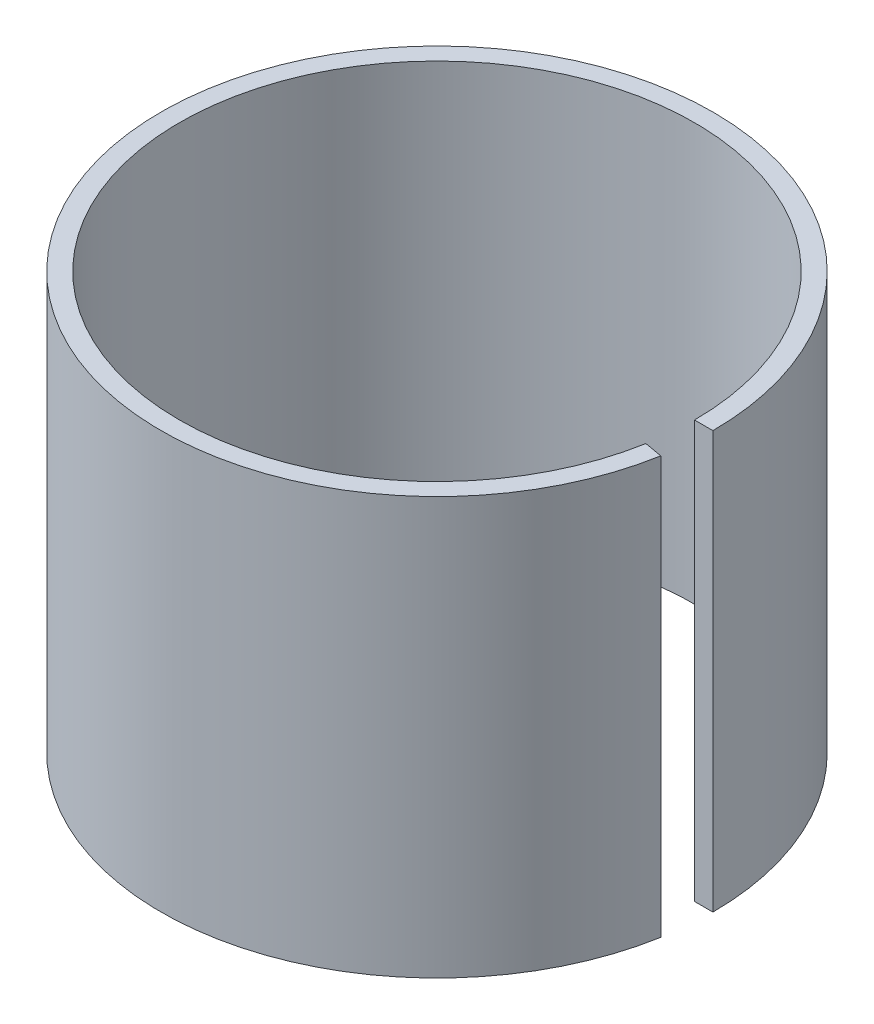
SolidWorks part; units mm, degrees
material "Alumina"
ref_plane "Front Plane" through (0, 0, 0) normal (0, 0, 1) x (1, 0, 0)
ref_plane "Top Plane" through (0, 0, 0) normal (0, 1, 0) x (1, 0, 0)
ref_plane "Right Plane" through (0, 0, 0) normal (1, 0, 0) x (0, 0, -1)
sketch "Sketch1" plane through (0, 0, 0) normal (0, 0, 1) x (1, 0, 0)
  line L0 (0, 0) -> (21, 0) construction
  line L4 (0, 0) -> (0, 34) construction
  line L6 (21, 0) -> (21, 34)
  dimension "D1" = 34
  dimension "D2" = 21
revolve "Revolve-Thin1" add sketch "Sketch1" angle 350 about L4
